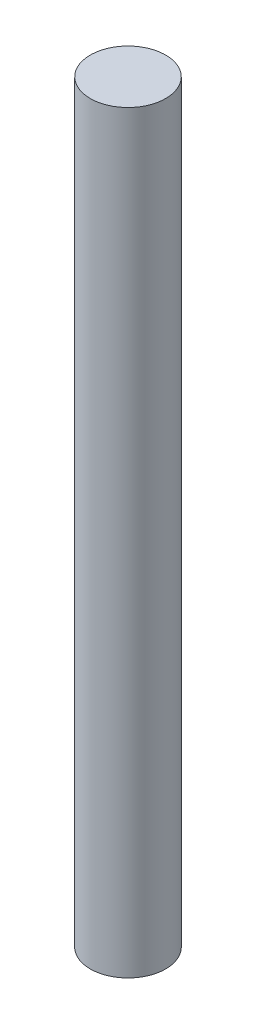
SolidWorks part; units mm, degrees
ref_plane "Front Plane" through (0, 0, 0) normal (0, 0, 1) x (1, 0, 0)
ref_plane "Top Plane" through (0, 0, 0) normal (0, 1, 0) x (1, 0, 0)
ref_plane "Right Plane" through (0, 0, 0) normal (1, 0, 0) x (0, 0, -1)
sketch "Sketch1" plane through (0, 0, 0) normal (0, 1, 0) x (1, 0, 0)
  circle A0 centre (-35.9589, 8.9231) radius 1
extrude "Boss-Extrude1" add sketch "Sketch1" along normal blind 20
